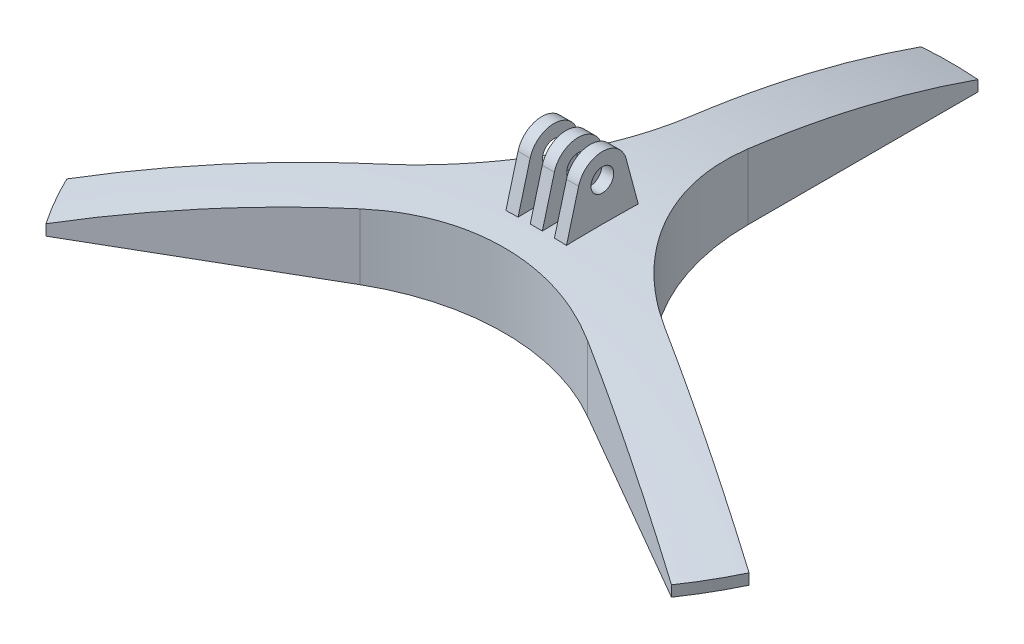
SolidWorks part; units mm, degrees
ref_plane "Front Plane" through (0, 0, 0) normal (0, 0, 1) x (1, 0, 0)
ref_plane "Top Plane" through (0, 0, 0) normal (0, 1, 0) x (1, 0, 0)
ref_plane "Right Plane" through (0, 0, 0) normal (1, 0, 0) x (0, 0, -1)
sketch "Sketch1" plane through (0, 0, 0) normal (0, 1, 0) x (1, 0, 0)
  line L0 (0, 0) -> (0, 105.5892) construction
  line L1 (-7.5, 99.7184) -> (-7.5, 38.9711)
  line L2 (7.5, 99.7184) -> (7.5, 38.9711)
  line L3 (-82.6086, -56.3544) -> (-30, -25.9808)
  line L4 (-90.1086, -43.364) -> (-37.5, -12.9904)
  line L5 (90.1086, -43.364) -> (37.5, -12.9904)
  line L6 (82.6086, -56.3544) -> (30, -25.9808)
  line L7 (0, 0) -> (121.9009, 0) construction
  arc A0 (-90.1086, -43.364) -> (-82.6086, -56.3544) centre (0, 0) ccw
  circle A1 centre (0, 0) radius 8.6603 construction
  arc A2 (7.5, 99.7184) -> (-7.5, 99.7184) centre (0, 0) ccw
  arc A3 (82.6086, -56.3544) -> (90.1086, -43.364) centre (0, 0) ccw
  arc A4 (-37.5, -12.9904) -> (-7.5, 38.9711) centre (-67.5, 38.9711) ccw
  arc A5 (-30, -25.9808) -> (30, -25.9808) centre (0, -77.9423) cw
  arc A6 (37.5, -12.9904) -> (7.5, 38.9711) centre (67.5, 38.9711) cw
  point P19 (0, 0)
  point P22 (-7.5, 4.3301)
  point P25 (0, -8.6603)
  point P28 (7.5, 4.3301)
  dimension "D1" = 200
  dimension "D6" = 60
  dimension "D2" = 15
  dimension "D3" = 120
  dimension "D4" = 15
  dimension "D5" = 15
extrude "Boss-Extrude1" add sketch "Sketch1" along normal blind 20 contours L4 A4 L1 A2 L2 A6 L5 A3 L6 A5 L3 A0
sketch "Sketch2" plane through (0, 0, 0) normal (0, 0, 1) x (1, 0, 0)
  line L0 (82.6086, 20) -> (30, 20) construction
  line L1 (0, 0) -> (0, 20) construction
  line L9 (30, 20) -> (-30, 20) construction
  line L10 (0, 20) -> (0, 34.9545)
  line L11 (0, 34.9545) -> (120, 34.9545)
  line L13 (120, -5.0455) -> (120, 34.9545)
  arc A0 (0, 20) -> (120, -5.0455) centre (0, -280) cw
  dimension "D1" = 40
  dimension "D3" = 240
  dimension "D2" = 300
revolve "Cut-Revolve4" cut sketch "Sketch2" angle 360 about L1
sketch "Sketch4" plane through (0, 0, 0) normal (1, 0, 0) x (0, 0, -1)
  line L0 (0, 0) -> (0, 46.4438) construction
  line L1 (-6.2785, 31.6823) -> (-9.9332, 18.0428)
  line L2 (6.2785, 31.6823) -> (9.5529, 19.462)
  arc A0 (6.2785, 31.6823) -> (-6.2785, 31.6823) centre (0, 30) ccw
  spline S0 degree 3 poles (1342.13, -1482.0389) (563.3107, -261.4273) (228.0609, -1.6091) (28.5858, 18.5297) (26.0312, 18.7489) (22.2357, 19.015) (20.9766, 19.0932) (18.4709, 19.2281) (17.2379, 19.2841) (13.6014, 19.4181) (11.2581, 19.4627) (6.7318, 19.4633) (4.5486, 19.4194) (1.3988, 19.2845) (0.38, 19.2285) (-1.5912, 19.0949) (-2.5447, 19.0174) (-5.3102, 18.7531) (-7.0277, 18.5348) (-9.4138, 18.1433) (-10.1774, 18.0021) (-98.3885, -0.358) (344.4256, -162.2689) (1966.3151, -243.6238) knots -9.420643 -9.420643 -9.420643 -9.420643 0.125 0.125 0.25 0.25 0.3125 0.3125 0.375 0.375 0.5 0.5 0.625 0.625 0.6875 0.6875 0.75 0.75 0.875 0.875 0.9375 0.9375 8.415798 8.415798 8.415798 8.415798 only from (38.9711, 17.3634) to (-12.9904, 17.3634) construction
  spline S1 degree 3 poles (9.5529, 19.462) (9.3664, 19.4626) (6.9107, 19.4669) (4.5486, 19.4194) (1.3988, 19.2845) (0.38, 19.2285) (-1.5912, 19.0949) (-2.5447, 19.0174) (-5.3102, 18.7531) (-7.0277, 18.5348) (-9.0668, 18.2002) (-9.5051, 18.1232) (-9.9332, 18.0428) knots 0.489757 0.489757 0.489757 0.489757 0.5 0.625 0.625 0.6875 0.6875 0.75 0.75 0.875 0.875 0.910235 0.910235 0.910235 0.910235
  dimension "D1" = 13
  dimension "D2" = 30
  dimension "D3" = 30
extrude "Boss-Extrude2" add sketch "Sketch4" along normal mid plane 3.2 separate body
move or copy body "Body-Move/Copy2" bodies to move or copy 106 copy yes number of copies 1 translate (6.4, 0, 0)
move or copy body "Body-Move/Copy3" bodies to move or copy 106 copy yes number of copies 1 translate (-6.4, 0, 0)
sketch "Sketch5" plane through (8, 0, 0) normal (1, 0, 0) x (0, 0, -1)
  circle A0 centre (0, 30) radius 3
  arc A1 (6.2785, 31.6823) -> (-6.2785, 31.6823) centre (0, 30) ccw construction
  dimension "D1" = 6
extrude "Cut-Extrude1" cut sketch "Sketch5" against normal through all
sketch "Sketch6" plane through (-8, 0, 0) normal (-1, 0, 0) x (0, 0, 1)
  circle A1 centre (0, 30) radius 5.25
  dimension "D1" = 10.5
extrude "Cut-Extrude2" cut sketch "Sketch6" against normal blind 2
